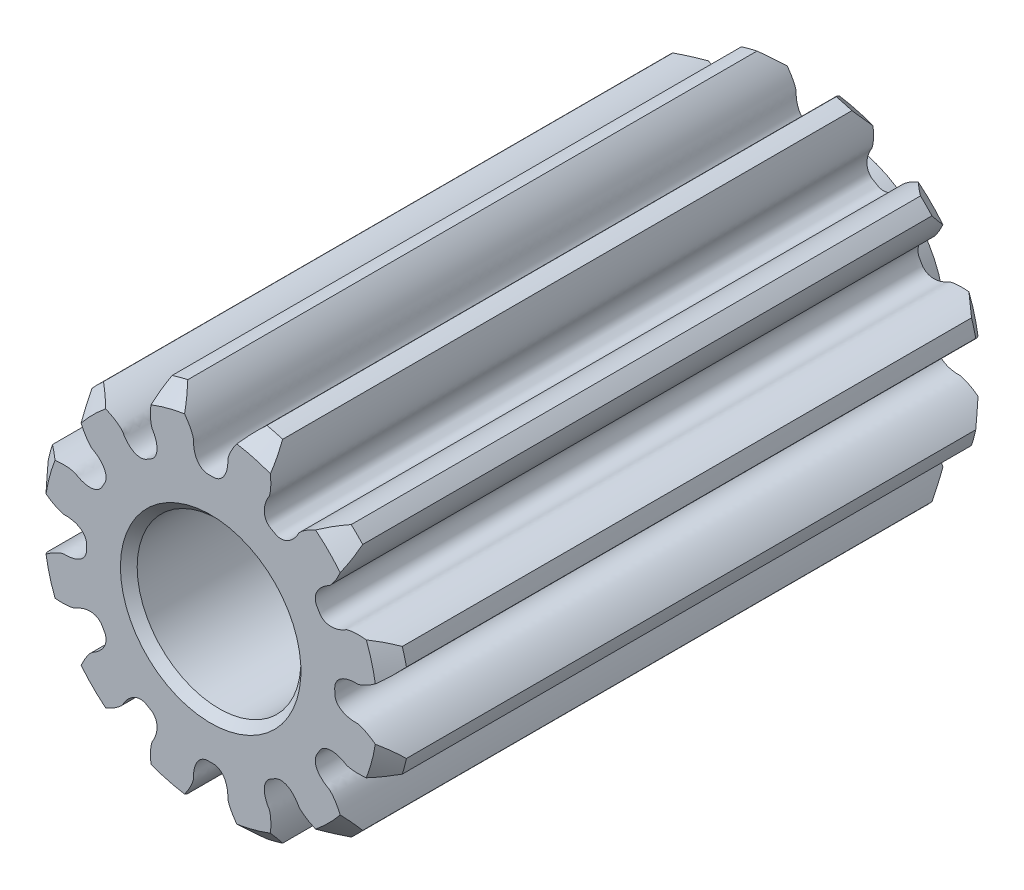
SolidWorks part; units mm, degrees
material "Plain Carbon Steel"
ref_plane "Front Plane" through (0, 0, 0) normal (0, 0, 1) x (1, 0, 0)
ref_plane "Top Plane" through (0, 0, 0) normal (0, 1, 0) x (1, 0, 0)
ref_plane "Right Plane" through (0, 0, 0) normal (1, 0, 0) x (0, 0, -1)
ref_plane "Plane1" through (0, 0, -9.1281) normal (0, 0, -1) x (-1, 0, 0)
sketch "Sketch1" plane through (0, 0, -9.1281) normal (0, 0, -1) x (-1, 0, 0)
  arc A0 (5.4254, 1.1987) -> (5.2979, 1.6746) centre (0, 0) ccw
  arc A1 (4.0992, 3.7508) -> (3.7508, 4.0992) centre (0, 0) ccw
  arc A2 (1.6746, 5.2979) -> (1.1987, 5.4254) centre (0, 0) ccw
  arc A3 (-1.1987, 5.4254) -> (-1.6746, 5.2979) centre (0, 0) ccw
  arc A4 (-3.7508, 4.0992) -> (-4.0992, 3.7508) centre (0, 0) ccw
  arc A5 (-5.2979, 1.6746) -> (-5.4254, 1.1987) centre (0, 0) ccw
  arc A6 (-5.4254, -1.1987) -> (-5.2979, -1.6746) centre (0, 0) ccw
  arc A7 (-4.0992, -3.7508) -> (-3.7508, -4.0992) centre (0, 0) ccw
  arc A8 (-1.6746, -5.2979) -> (-1.1987, -5.4254) centre (0, 0) ccw
  arc A9 (1.1987, -5.4254) -> (1.6746, -5.2979) centre (0, 0) ccw
  arc A10 (3.7508, -4.0992) -> (4.0992, -3.7508) centre (0, 0) ccw
  arc A11 (5.2979, -1.6746) -> (5.4254, -1.1987) centre (0, 0) ccw
  spline S0 degree 3 poles (5.4254, 1.1987) (5.3837, 1.151) (5.3155, 1.0775) (5.219, 0.9833) (5.1419, 0.9135) (5.067, 0.8507) (4.9949, 0.7945) (4.9257, 0.7448) (4.8601, 0.7012) (4.7982, 0.6634) (4.7404, 0.6311) (4.6871, 0.6037) (4.6385, 0.5811) (4.5949, 0.5628) (4.5566, 0.5482) (4.5124, 0.5337) (4.4425, 0.5115) (4.3737, 0.5215) (4.3208, 0.5172) (4.3005, 0.5154) (4.2805, 0.5133) (4.2608, 0.5108) (4.2414, 0.508) (4.2222, 0.5048) (4.2033, 0.5013) (4.1847, 0.4975) (4.1664, 0.4933) (4.1483, 0.4888) (4.1305, 0.4839) (4.1129, 0.4787) (4.0957, 0.4731) (4.0787, 0.4672) (4.0619, 0.4609) (4.0454, 0.4542) (4.0292, 0.4471) (4.0133, 0.4396) (3.9976, 0.4317) (3.9821, 0.4233) (3.967, 0.4145) (3.9521, 0.4052) (3.9375, 0.3954) (3.9231, 0.3851) (3.9091, 0.3742) (3.8954, 0.3627) (3.8821, 0.3507) (3.8691, 0.338) (3.8565, 0.3246) (3.8444, 0.3106) (3.8328, 0.2958) (3.8217, 0.2802) (3.8112, 0.264) (3.8014, 0.2469) (3.7925, 0.2291) (3.7843, 0.2106) (3.7771, 0.1913) (3.771, 0.1714) (3.766, 0.151) (3.7622, 0.13) (3.7597, 0.1087) (3.7586, 0.0894) (3.7583, 0.0531) (3.7599, 0) (3.7583, -0.0531) (3.7586, -0.0894) (3.7597, -0.1087) (3.7622, -0.13) (3.766, -0.151) (3.771, -0.1714) (3.7771, -0.1913) (3.7843, -0.2106) (3.7925, -0.2291) (3.8014, -0.2469) (3.8112, -0.264) (3.8217, -0.2802) (3.8328, -0.2958) (3.8444, -0.3106) (3.8565, -0.3246) (3.8691, -0.338) (3.8821, -0.3507) (3.8954, -0.3627) (3.9091, -0.3742) (3.9231, -0.3851) (3.9375, -0.3954) (3.9521, -0.4052) (3.967, -0.4145) (3.9821, -0.4233) (3.9976, -0.4317) (4.0133, -0.4396) (4.0292, -0.4471) (4.0454, -0.4542) (4.0619, -0.4609) (4.0787, -0.4672) (4.0957, -0.4731) (4.1129, -0.4787) (4.1305, -0.4839) (4.1483, -0.4888) (4.1664, -0.4933) (4.1847, -0.4975) (4.2033, -0.5013) (4.2222, -0.5048) (4.2414, -0.508) (4.2608, -0.5108) (4.2805, -0.5133) (4.3005, -0.5154) (4.3208, -0.5172) (4.3737, -0.5215) (4.4425, -0.5115) (4.5124, -0.5337) (4.5566, -0.5482) (4.5949, -0.5628) (4.6385, -0.5811) (4.6871, -0.6037) (4.7404, -0.6311) (4.7982, -0.6634) (4.8601, -0.7012) (4.9257, -0.7448) (4.9949, -0.7945) (5.067, -0.8507) (5.1419, -0.9135) (5.219, -0.9833) (5.3155, -1.0775) (5.3837, -1.151) (5.4254, -1.1987) knots 0 0 0 0 0.042267 0.066794 0.08992 0.111644 0.131967 0.150888 0.168407 0.184525 0.199242 0.212557 0.22447 0.234982 0.244092 0.251801 0.266087 0.292386 0.296963 0.301485 0.305953 0.31037 0.314735 0.319052 0.323321 0.327546 0.331727 0.335868 0.339971 0.344037 0.348071 0.352075 0.356052 0.360006 0.36394 0.367858 0.371765 0.375665 0.379562 0.383462 0.387371 0.391292 0.395233 0.399199 0.403196 0.407229 0.411306 0.415432 0.419611 0.423849 0.42815 0.432515 0.436948 0.441448 0.446012 0.450638 0.45532 0.460051 0.464821 0.469619 0.472951 0.489007 0.505064 0.508396 0.513194 0.517964 0.522694 0.527376 0.532002 0.536567 0.541066 0.545499 0.549865 0.554165 0.558403 0.562583 0.566708 0.570785 0.574819 0.578816 0.582782 0.586722 0.590644 0.594552 0.598452 0.60235 0.60625 0.610156 0.614075 0.618009 0.621963 0.62594 0.629943 0.633977 0.638044 0.642146 0.646287 0.650469 0.654693 0.658963 0.663279 0.667645 0.672061 0.676529 0.681051 0.685628 0.711928 0.726214 0.733923 0.743033 0.753545 0.765458 0.778773 0.793489 0.809607 0.827127 0.846048 0.86637 0.888095 0.91122 0.935748 0.978015 0.978015 0.978015 0.978015
  spline S1 degree 3 poles (4.0992, 3.7508) (4.0869, 3.6886) (4.0646, 3.5909) (4.0281, 3.4611) (3.9963, 3.3621) (3.9629, 3.2702) (3.9284, 3.1855) (3.8934, 3.1079) (3.8583, 3.0373) (3.8236, 2.9736) (3.7898, 2.9167) (3.7573, 2.8664) (3.7265, 2.8225) (3.698, 2.7848) (3.6721, 2.753) (3.641, 2.7184) (3.5916, 2.6642) (3.5269, 2.6385) (3.4833, 2.6083) (3.4666, 2.5966) (3.4504, 2.5848) (3.4346, 2.5728) (3.4191, 2.5606) (3.4041, 2.5483) (3.3895, 2.5358) (3.3753, 2.5232) (3.3615, 2.5104) (3.3481, 2.4975) (3.3351, 2.4843) (3.3225, 2.4711) (3.3104, 2.4576) (3.2986, 2.4439) (3.2873, 2.4301) (3.2764, 2.416) (3.2659, 2.4018) (3.2558, 2.3873) (3.2462, 2.3726) (3.237, 2.3576) (3.2283, 2.3424) (3.22, 2.3269) (3.2122, 2.3111) (3.205, 2.295) (3.1983, 2.2786) (3.1922, 2.2619) (3.1866, 2.2447) (3.1817, 2.2272) (3.1775, 2.2094) (3.1741, 2.1911) (3.1714, 2.1725) (3.1695, 2.1535) (3.1686, 2.1342) (3.1687, 2.1146) (3.1698, 2.0946) (3.172, 2.0745) (3.1754, 2.0543) (3.1801, 2.034) (3.186, 2.0137) (3.1931, 1.9937) (3.2016, 1.974) (3.2104, 1.9567) (3.2282, 1.9252) (3.2562, 1.88) (3.2814, 1.8331) (3.2998, 1.8019) (3.3103, 1.7857) (3.3232, 1.7685) (3.3369, 1.7522) (3.3515, 1.737) (3.3668, 1.7229) (3.3826, 1.7098) (3.3989, 1.6978) (3.4156, 1.6869) (3.4326, 1.677) (3.4498, 1.6681) (3.4671, 1.6602) (3.4846, 1.6532) (3.5022, 1.6471) (3.5197, 1.6418) (3.5373, 1.6373) (3.5549, 1.6336) (3.5725, 1.6305) (3.5901, 1.6281) (3.6076, 1.6263) (3.6252, 1.6251) (3.6427, 1.6245) (3.6603, 1.6245) (3.6778, 1.625) (3.6954, 1.6259) (3.7129, 1.6274) (3.7305, 1.6294) (3.7482, 1.6318) (3.7658, 1.6347) (3.7835, 1.6381) (3.8013, 1.6419) (3.8191, 1.6461) (3.8369, 1.6508) (3.8548, 1.6559) (3.8728, 1.6615) (3.8908, 1.6675) (3.909, 1.6739) (3.9271, 1.6808) (3.9454, 1.688) (3.9637, 1.6957) (3.9821, 1.7039) (4.0005, 1.7125) (4.0485, 1.7352) (4.1031, 1.7783) (4.1747, 1.794) (4.2202, 1.8036) (4.2607, 1.8101) (4.3076, 1.816) (4.361, 1.8207) (4.4209, 1.8237) (4.4871, 1.8245) (4.5596, 1.8227) (4.6382, 1.8178) (4.7229, 1.8093) (4.8135, 1.7968) (4.9098, 1.7798) (5.0115, 1.7579) (5.1422, 1.7246) (5.2379, 1.695) (5.2979, 1.6746) knots 0 0 0 0 0.042267 0.066794 0.08992 0.111644 0.131967 0.150888 0.168407 0.184525 0.199242 0.212557 0.22447 0.234982 0.244092 0.251801 0.266087 0.292386 0.296963 0.301485 0.305953 0.31037 0.314735 0.319052 0.323321 0.327546 0.331727 0.335868 0.339971 0.344037 0.348071 0.352075 0.356052 0.360006 0.36394 0.367858 0.371765 0.375665 0.379562 0.383462 0.387371 0.391292 0.395233 0.399199 0.403196 0.407229 0.411306 0.415432 0.419611 0.423849 0.42815 0.432515 0.436948 0.441448 0.446012 0.450638 0.45532 0.460051 0.464821 0.469619 0.472951 0.489007 0.505064 0.508396 0.513194 0.517964 0.522694 0.527376 0.532002 0.536567 0.541066 0.545499 0.549865 0.554165 0.558403 0.562583 0.566708 0.570785 0.574819 0.578816 0.582782 0.586722 0.590644 0.594552 0.598452 0.60235 0.60625 0.610156 0.614075 0.618009 0.621963 0.62594 0.629943 0.633977 0.638044 0.642146 0.646287 0.650469 0.654693 0.658963 0.663279 0.667645 0.672061 0.676529 0.681051 0.685628 0.711928 0.726214 0.733923 0.743033 0.753545 0.765458 0.778773 0.793489 0.809607 0.827127 0.846048 0.86637 0.888095 0.91122 0.935748 0.978015 0.978015 0.978015 0.978015
  spline S2 degree 3 poles (1.6746, 5.2979) (1.695, 5.2379) (1.7246, 5.1422) (1.7579, 5.0115) (1.7798, 4.9098) (1.7968, 4.8135) (1.8093, 4.7229) (1.8178, 4.6382) (1.8227, 4.5596) (1.8245, 4.4871) (1.8237, 4.4209) (1.8207, 4.361) (1.816, 4.3076) (1.8101, 4.2607) (1.8036, 4.2202) (1.794, 4.1747) (1.7783, 4.1031) (1.7352, 4.0485) (1.7125, 4.0005) (1.7039, 3.9821) (1.6957, 3.9637) (1.688, 3.9454) (1.6808, 3.9271) (1.6739, 3.909) (1.6675, 3.8908) (1.6615, 3.8728) (1.6559, 3.8548) (1.6508, 3.8369) (1.6461, 3.8191) (1.6419, 3.8013) (1.6381, 3.7835) (1.6347, 3.7658) (1.6318, 3.7482) (1.6294, 3.7305) (1.6274, 3.7129) (1.6259, 3.6954) (1.625, 3.6778) (1.6245, 3.6603) (1.6245, 3.6427) (1.6251, 3.6252) (1.6263, 3.6076) (1.6281, 3.5901) (1.6305, 3.5725) (1.6336, 3.5549) (1.6373, 3.5373) (1.6418, 3.5197) (1.6471, 3.5022) (1.6532, 3.4846) (1.6602, 3.4671) (1.6681, 3.4498) (1.677, 3.4326) (1.6869, 3.4156) (1.6978, 3.3989) (1.7098, 3.3826) (1.7229, 3.3668) (1.737, 3.3515) (1.7522, 3.3369) (1.7685, 3.3232) (1.7857, 3.3103) (1.8019, 3.2998) (1.8331, 3.2814) (1.88, 3.2562) (1.9252, 3.2282) (1.9567, 3.2104) (1.974, 3.2016) (1.9937, 3.1931) (2.0137, 3.186) (2.034, 3.1801) (2.0543, 3.1754) (2.0745, 3.172) (2.0946, 3.1698) (2.1146, 3.1687) (2.1342, 3.1686) (2.1535, 3.1695) (2.1725, 3.1714) (2.1911, 3.1741) (2.2094, 3.1775) (2.2272, 3.1817) (2.2447, 3.1866) (2.2619, 3.1922) (2.2786, 3.1983) (2.295, 3.205) (2.3111, 3.2122) (2.3269, 3.22) (2.3424, 3.2283) (2.3576, 3.237) (2.3726, 3.2462) (2.3873, 3.2558) (2.4018, 3.2659) (2.416, 3.2764) (2.4301, 3.2873) (2.4439, 3.2986) (2.4576, 3.3104) (2.4711, 3.3225) (2.4843, 3.3351) (2.4975, 3.3481) (2.5104, 3.3615) (2.5232, 3.3753) (2.5358, 3.3895) (2.5483, 3.4041) (2.5606, 3.4191) (2.5728, 3.4346) (2.5848, 3.4504) (2.5966, 3.4666) (2.6083, 3.4833) (2.6385, 3.5269) (2.6642, 3.5916) (2.7184, 3.641) (2.753, 3.6721) (2.7848, 3.698) (2.8225, 3.7265) (2.8664, 3.7573) (2.9167, 3.7898) (2.9736, 3.8236) (3.0373, 3.8583) (3.1079, 3.8934) (3.1855, 3.9284) (3.2702, 3.9629) (3.3621, 3.9963) (3.4611, 4.0281) (3.5909, 4.0646) (3.6886, 4.0869) (3.7508, 4.0992) knots 0 0 0 0 0.042267 0.066794 0.08992 0.111644 0.131967 0.150888 0.168407 0.184525 0.199242 0.212557 0.22447 0.234982 0.244092 0.251801 0.266087 0.292386 0.296963 0.301485 0.305953 0.31037 0.314735 0.319052 0.323321 0.327546 0.331727 0.335868 0.339971 0.344037 0.348071 0.352075 0.356052 0.360006 0.36394 0.367858 0.371765 0.375665 0.379562 0.383462 0.387371 0.391292 0.395233 0.399199 0.403196 0.407229 0.411306 0.415432 0.419611 0.423849 0.42815 0.432515 0.436948 0.441448 0.446012 0.450638 0.45532 0.460051 0.464821 0.469619 0.472951 0.489007 0.505064 0.508396 0.513194 0.517964 0.522694 0.527376 0.532002 0.536567 0.541066 0.545499 0.549865 0.554165 0.558403 0.562583 0.566708 0.570785 0.574819 0.578816 0.582782 0.586722 0.590644 0.594552 0.598452 0.60235 0.60625 0.610156 0.614075 0.618009 0.621963 0.62594 0.629943 0.633977 0.638044 0.642146 0.646287 0.650469 0.654693 0.658963 0.663279 0.667645 0.672061 0.676529 0.681051 0.685628 0.711928 0.726214 0.733923 0.743033 0.753545 0.765458 0.778773 0.793489 0.809607 0.827127 0.846048 0.86637 0.888095 0.91122 0.935748 0.978015 0.978015 0.978015 0.978015
  spline S3 degree 3 poles (-1.1987, 5.4254) (-1.151, 5.3837) (-1.0775, 5.3155) (-0.9833, 5.219) (-0.9135, 5.1419) (-0.8507, 5.067) (-0.7945, 4.9949) (-0.7448, 4.9257) (-0.7012, 4.8601) (-0.6634, 4.7982) (-0.6311, 4.7404) (-0.6037, 4.6871) (-0.5811, 4.6385) (-0.5628, 4.5949) (-0.5482, 4.5566) (-0.5337, 4.5124) (-0.5115, 4.4425) (-0.5215, 4.3737) (-0.5172, 4.3208) (-0.5154, 4.3005) (-0.5133, 4.2805) (-0.5108, 4.2608) (-0.508, 4.2414) (-0.5048, 4.2222) (-0.5013, 4.2033) (-0.4975, 4.1847) (-0.4933, 4.1664) (-0.4888, 4.1483) (-0.4839, 4.1305) (-0.4787, 4.1129) (-0.4731, 4.0957) (-0.4672, 4.0787) (-0.4609, 4.0619) (-0.4542, 4.0454) (-0.4471, 4.0292) (-0.4396, 4.0133) (-0.4317, 3.9976) (-0.4233, 3.9821) (-0.4145, 3.967) (-0.4052, 3.9521) (-0.3954, 3.9375) (-0.3851, 3.9231) (-0.3742, 3.9091) (-0.3627, 3.8954) (-0.3507, 3.8821) (-0.338, 3.8691) (-0.3246, 3.8565) (-0.3106, 3.8444) (-0.2958, 3.8328) (-0.2802, 3.8217) (-0.264, 3.8112) (-0.2469, 3.8014) (-0.2291, 3.7925) (-0.2106, 3.7843) (-0.1913, 3.7771) (-0.1714, 3.771) (-0.151, 3.766) (-0.13, 3.7622) (-0.1087, 3.7597) (-0.0894, 3.7586) (-0.0531, 3.7583) (0, 3.7599) (0.0531, 3.7583) (0.0894, 3.7586) (0.1087, 3.7597) (0.13, 3.7622) (0.151, 3.766) (0.1714, 3.771) (0.1913, 3.7771) (0.2106, 3.7843) (0.2291, 3.7925) (0.2469, 3.8014) (0.264, 3.8112) (0.2802, 3.8217) (0.2958, 3.8328) (0.3106, 3.8444) (0.3246, 3.8565) (0.338, 3.8691) (0.3507, 3.8821) (0.3627, 3.8954) (0.3742, 3.9091) (0.3851, 3.9231) (0.3954, 3.9375) (0.4052, 3.9521) (0.4145, 3.967) (0.4233, 3.9821) (0.4317, 3.9976) (0.4396, 4.0133) (0.4471, 4.0292) (0.4542, 4.0454) (0.4609, 4.0619) (0.4672, 4.0787) (0.4731, 4.0957) (0.4787, 4.1129) (0.4839, 4.1305) (0.4888, 4.1483) (0.4933, 4.1664) (0.4975, 4.1847) (0.5013, 4.2033) (0.5048, 4.2222) (0.508, 4.2414) (0.5108, 4.2608) (0.5133, 4.2805) (0.5154, 4.3005) (0.5172, 4.3208) (0.5215, 4.3737) (0.5115, 4.4425) (0.5337, 4.5124) (0.5482, 4.5566) (0.5628, 4.5949) (0.5811, 4.6385) (0.6037, 4.6871) (0.6311, 4.7404) (0.6634, 4.7982) (0.7012, 4.8601) (0.7448, 4.9257) (0.7945, 4.9949) (0.8507, 5.067) (0.9135, 5.1419) (0.9833, 5.219) (1.0775, 5.3155) (1.151, 5.3837) (1.1987, 5.4254) knots 0 0 0 0 0.042267 0.066794 0.08992 0.111644 0.131967 0.150888 0.168407 0.184525 0.199242 0.212557 0.22447 0.234982 0.244092 0.251801 0.266087 0.292386 0.296963 0.301485 0.305953 0.31037 0.314735 0.319052 0.323321 0.327546 0.331727 0.335868 0.339971 0.344037 0.348071 0.352075 0.356052 0.360006 0.36394 0.367858 0.371765 0.375665 0.379562 0.383462 0.387371 0.391292 0.395233 0.399199 0.403196 0.407229 0.411306 0.415432 0.419611 0.423849 0.42815 0.432515 0.436948 0.441448 0.446012 0.450638 0.45532 0.460051 0.464821 0.469619 0.472951 0.489007 0.505064 0.508396 0.513194 0.517964 0.522694 0.527376 0.532002 0.536567 0.541066 0.545499 0.549865 0.554165 0.558403 0.562583 0.566708 0.570785 0.574819 0.578816 0.582782 0.586722 0.590644 0.594552 0.598452 0.60235 0.60625 0.610156 0.614075 0.618009 0.621963 0.62594 0.629943 0.633977 0.638044 0.642146 0.646287 0.650469 0.654693 0.658963 0.663279 0.667645 0.672061 0.676529 0.681051 0.685628 0.711928 0.726214 0.733923 0.743033 0.753545 0.765458 0.778773 0.793489 0.809607 0.827127 0.846048 0.86637 0.888095 0.91122 0.935748 0.978015 0.978015 0.978015 0.978015
  spline S4 degree 3 poles (-3.7508, 4.0992) (-3.6886, 4.0869) (-3.5909, 4.0646) (-3.4611, 4.0281) (-3.3621, 3.9963) (-3.2702, 3.9629) (-3.1855, 3.9284) (-3.1079, 3.8934) (-3.0373, 3.8583) (-2.9736, 3.8236) (-2.9167, 3.7898) (-2.8664, 3.7573) (-2.8225, 3.7265) (-2.7848, 3.698) (-2.753, 3.6721) (-2.7184, 3.641) (-2.6642, 3.5916) (-2.6385, 3.5269) (-2.6083, 3.4833) (-2.5966, 3.4666) (-2.5848, 3.4504) (-2.5728, 3.4346) (-2.5606, 3.4191) (-2.5483, 3.4041) (-2.5358, 3.3895) (-2.5232, 3.3753) (-2.5104, 3.3615) (-2.4975, 3.3481) (-2.4843, 3.3351) (-2.4711, 3.3225) (-2.4576, 3.3104) (-2.4439, 3.2986) (-2.4301, 3.2873) (-2.416, 3.2764) (-2.4018, 3.2659) (-2.3873, 3.2558) (-2.3726, 3.2462) (-2.3576, 3.237) (-2.3424, 3.2283) (-2.3269, 3.22) (-2.3111, 3.2122) (-2.295, 3.205) (-2.2786, 3.1983) (-2.2619, 3.1922) (-2.2447, 3.1866) (-2.2272, 3.1817) (-2.2094, 3.1775) (-2.1911, 3.1741) (-2.1725, 3.1714) (-2.1535, 3.1695) (-2.1342, 3.1686) (-2.1146, 3.1687) (-2.0946, 3.1698) (-2.0745, 3.172) (-2.0543, 3.1754) (-2.034, 3.1801) (-2.0137, 3.186) (-1.9937, 3.1931) (-1.974, 3.2016) (-1.9567, 3.2104) (-1.9252, 3.2282) (-1.88, 3.2562) (-1.8331, 3.2814) (-1.8019, 3.2998) (-1.7857, 3.3103) (-1.7685, 3.3232) (-1.7522, 3.3369) (-1.737, 3.3515) (-1.7229, 3.3668) (-1.7098, 3.3826) (-1.6978, 3.3989) (-1.6869, 3.4156) (-1.677, 3.4326) (-1.6681, 3.4498) (-1.6602, 3.4671) (-1.6532, 3.4846) (-1.6471, 3.5022) (-1.6418, 3.5197) (-1.6373, 3.5373) (-1.6336, 3.5549) (-1.6305, 3.5725) (-1.6281, 3.5901) (-1.6263, 3.6076) (-1.6251, 3.6252) (-1.6245, 3.6427) (-1.6245, 3.6603) (-1.625, 3.6778) (-1.6259, 3.6954) (-1.6274, 3.7129) (-1.6294, 3.7305) (-1.6318, 3.7482) (-1.6347, 3.7658) (-1.6381, 3.7835) (-1.6419, 3.8013) (-1.6461, 3.8191) (-1.6508, 3.8369) (-1.6559, 3.8548) (-1.6615, 3.8728) (-1.6675, 3.8908) (-1.6739, 3.909) (-1.6808, 3.9271) (-1.688, 3.9454) (-1.6957, 3.9637) (-1.7039, 3.9821) (-1.7125, 4.0005) (-1.7352, 4.0485) (-1.7783, 4.1031) (-1.794, 4.1747) (-1.8036, 4.2202) (-1.8101, 4.2607) (-1.816, 4.3076) (-1.8207, 4.361) (-1.8237, 4.4209) (-1.8245, 4.4871) (-1.8227, 4.5596) (-1.8178, 4.6382) (-1.8093, 4.7229) (-1.7968, 4.8135) (-1.7798, 4.9098) (-1.7579, 5.0115) (-1.7246, 5.1422) (-1.695, 5.2379) (-1.6746, 5.2979) knots 0 0 0 0 0.042267 0.066794 0.08992 0.111644 0.131967 0.150888 0.168407 0.184525 0.199242 0.212557 0.22447 0.234982 0.244092 0.251801 0.266087 0.292386 0.296963 0.301485 0.305953 0.31037 0.314735 0.319052 0.323321 0.327546 0.331727 0.335868 0.339971 0.344037 0.348071 0.352075 0.356052 0.360006 0.36394 0.367858 0.371765 0.375665 0.379562 0.383462 0.387371 0.391292 0.395233 0.399199 0.403196 0.407229 0.411306 0.415432 0.419611 0.423849 0.42815 0.432515 0.436948 0.441448 0.446012 0.450638 0.45532 0.460051 0.464821 0.469619 0.472951 0.489007 0.505064 0.508396 0.513194 0.517964 0.522694 0.527376 0.532002 0.536567 0.541066 0.545499 0.549865 0.554165 0.558403 0.562583 0.566708 0.570785 0.574819 0.578816 0.582782 0.586722 0.590644 0.594552 0.598452 0.60235 0.60625 0.610156 0.614075 0.618009 0.621963 0.62594 0.629943 0.633977 0.638044 0.642146 0.646287 0.650469 0.654693 0.658963 0.663279 0.667645 0.672061 0.676529 0.681051 0.685628 0.711928 0.726214 0.733923 0.743033 0.753545 0.765458 0.778773 0.793489 0.809607 0.827127 0.846048 0.86637 0.888095 0.91122 0.935748 0.978015 0.978015 0.978015 0.978015
  spline S5 degree 3 poles (-5.2979, 1.6746) (-5.2379, 1.695) (-5.1422, 1.7246) (-5.0115, 1.7579) (-4.9098, 1.7798) (-4.8135, 1.7968) (-4.7229, 1.8093) (-4.6382, 1.8178) (-4.5596, 1.8227) (-4.4871, 1.8245) (-4.4209, 1.8237) (-4.361, 1.8207) (-4.3076, 1.816) (-4.2607, 1.8101) (-4.2202, 1.8036) (-4.1747, 1.794) (-4.1031, 1.7783) (-4.0485, 1.7352) (-4.0005, 1.7125) (-3.9821, 1.7039) (-3.9637, 1.6957) (-3.9454, 1.688) (-3.9271, 1.6808) (-3.909, 1.6739) (-3.8908, 1.6675) (-3.8728, 1.6615) (-3.8548, 1.6559) (-3.8369, 1.6508) (-3.8191, 1.6461) (-3.8013, 1.6419) (-3.7835, 1.6381) (-3.7658, 1.6347) (-3.7482, 1.6318) (-3.7305, 1.6294) (-3.7129, 1.6274) (-3.6954, 1.6259) (-3.6778, 1.625) (-3.6603, 1.6245) (-3.6427, 1.6245) (-3.6252, 1.6251) (-3.6076, 1.6263) (-3.5901, 1.6281) (-3.5725, 1.6305) (-3.5549, 1.6336) (-3.5373, 1.6373) (-3.5197, 1.6418) (-3.5022, 1.6471) (-3.4846, 1.6532) (-3.4671, 1.6602) (-3.4498, 1.6681) (-3.4326, 1.677) (-3.4156, 1.6869) (-3.3989, 1.6978) (-3.3826, 1.7098) (-3.3668, 1.7229) (-3.3515, 1.737) (-3.3369, 1.7522) (-3.3232, 1.7685) (-3.3103, 1.7857) (-3.2998, 1.8019) (-3.2814, 1.8331) (-3.2562, 1.88) (-3.2282, 1.9252) (-3.2104, 1.9567) (-3.2016, 1.974) (-3.1931, 1.9937) (-3.186, 2.0137) (-3.1801, 2.034) (-3.1754, 2.0543) (-3.172, 2.0745) (-3.1698, 2.0946) (-3.1687, 2.1146) (-3.1686, 2.1342) (-3.1695, 2.1535) (-3.1714, 2.1725) (-3.1741, 2.1911) (-3.1775, 2.2094) (-3.1817, 2.2272) (-3.1866, 2.2447) (-3.1922, 2.2619) (-3.1983, 2.2786) (-3.205, 2.295) (-3.2122, 2.3111) (-3.22, 2.3269) (-3.2283, 2.3424) (-3.237, 2.3576) (-3.2462, 2.3726) (-3.2558, 2.3873) (-3.2659, 2.4018) (-3.2764, 2.416) (-3.2873, 2.4301) (-3.2986, 2.4439) (-3.3104, 2.4576) (-3.3225, 2.4711) (-3.3351, 2.4843) (-3.3481, 2.4975) (-3.3615, 2.5104) (-3.3753, 2.5232) (-3.3895, 2.5358) (-3.4041, 2.5483) (-3.4191, 2.5606) (-3.4346, 2.5728) (-3.4504, 2.5848) (-3.4666, 2.5966) (-3.4833, 2.6083) (-3.5269, 2.6385) (-3.5916, 2.6642) (-3.641, 2.7184) (-3.6721, 2.753) (-3.698, 2.7848) (-3.7265, 2.8225) (-3.7573, 2.8664) (-3.7898, 2.9167) (-3.8236, 2.9736) (-3.8583, 3.0373) (-3.8934, 3.1079) (-3.9284, 3.1855) (-3.9629, 3.2702) (-3.9963, 3.3621) (-4.0281, 3.4611) (-4.0646, 3.5909) (-4.0869, 3.6886) (-4.0992, 3.7508) knots 0 0 0 0 0.042267 0.066794 0.08992 0.111644 0.131967 0.150888 0.168407 0.184525 0.199242 0.212557 0.22447 0.234982 0.244092 0.251801 0.266087 0.292386 0.296963 0.301485 0.305953 0.31037 0.314735 0.319052 0.323321 0.327546 0.331727 0.335868 0.339971 0.344037 0.348071 0.352075 0.356052 0.360006 0.36394 0.367858 0.371765 0.375665 0.379562 0.383462 0.387371 0.391292 0.395233 0.399199 0.403196 0.407229 0.411306 0.415432 0.419611 0.423849 0.42815 0.432515 0.436948 0.441448 0.446012 0.450638 0.45532 0.460051 0.464821 0.469619 0.472951 0.489007 0.505064 0.508396 0.513194 0.517964 0.522694 0.527376 0.532002 0.536567 0.541066 0.545499 0.549865 0.554165 0.558403 0.562583 0.566708 0.570785 0.574819 0.578816 0.582782 0.586722 0.590644 0.594552 0.598452 0.60235 0.60625 0.610156 0.614075 0.618009 0.621963 0.62594 0.629943 0.633977 0.638044 0.642146 0.646287 0.650469 0.654693 0.658963 0.663279 0.667645 0.672061 0.676529 0.681051 0.685628 0.711928 0.726214 0.733923 0.743033 0.753545 0.765458 0.778773 0.793489 0.809607 0.827127 0.846048 0.86637 0.888095 0.91122 0.935748 0.978015 0.978015 0.978015 0.978015
  spline S6 degree 3 poles (-5.4254, -1.1987) (-5.3837, -1.151) (-5.3155, -1.0775) (-5.219, -0.9833) (-5.1419, -0.9135) (-5.067, -0.8507) (-4.9949, -0.7945) (-4.9257, -0.7448) (-4.8601, -0.7012) (-4.7982, -0.6634) (-4.7404, -0.6311) (-4.6871, -0.6037) (-4.6385, -0.5811) (-4.5949, -0.5628) (-4.5566, -0.5482) (-4.5124, -0.5337) (-4.4425, -0.5115) (-4.3737, -0.5215) (-4.3208, -0.5172) (-4.3005, -0.5154) (-4.2805, -0.5133) (-4.2608, -0.5108) (-4.2414, -0.508) (-4.2222, -0.5048) (-4.2033, -0.5013) (-4.1847, -0.4975) (-4.1664, -0.4933) (-4.1483, -0.4888) (-4.1305, -0.4839) (-4.1129, -0.4787) (-4.0957, -0.4731) (-4.0787, -0.4672) (-4.0619, -0.4609) (-4.0454, -0.4542) (-4.0292, -0.4471) (-4.0133, -0.4396) (-3.9976, -0.4317) (-3.9821, -0.4233) (-3.967, -0.4145) (-3.9521, -0.4052) (-3.9375, -0.3954) (-3.9231, -0.3851) (-3.9091, -0.3742) (-3.8954, -0.3627) (-3.8821, -0.3507) (-3.8691, -0.338) (-3.8565, -0.3246) (-3.8444, -0.3106) (-3.8328, -0.2958) (-3.8217, -0.2802) (-3.8112, -0.264) (-3.8014, -0.2469) (-3.7925, -0.2291) (-3.7843, -0.2106) (-3.7771, -0.1913) (-3.771, -0.1714) (-3.766, -0.151) (-3.7622, -0.13) (-3.7597, -0.1087) (-3.7586, -0.0894) (-3.7583, -0.0531) (-3.7599, 0) (-3.7583, 0.0531) (-3.7586, 0.0894) (-3.7597, 0.1087) (-3.7622, 0.13) (-3.766, 0.151) (-3.771, 0.1714) (-3.7771, 0.1913) (-3.7843, 0.2106) (-3.7925, 0.2291) (-3.8014, 0.2469) (-3.8112, 0.264) (-3.8217, 0.2802) (-3.8328, 0.2958) (-3.8444, 0.3106) (-3.8565, 0.3246) (-3.8691, 0.338) (-3.8821, 0.3507) (-3.8954, 0.3627) (-3.9091, 0.3742) (-3.9231, 0.3851) (-3.9375, 0.3954) (-3.9521, 0.4052) (-3.967, 0.4145) (-3.9821, 0.4233) (-3.9976, 0.4317) (-4.0133, 0.4396) (-4.0292, 0.4471) (-4.0454, 0.4542) (-4.0619, 0.4609) (-4.0787, 0.4672) (-4.0957, 0.4731) (-4.1129, 0.4787) (-4.1305, 0.4839) (-4.1483, 0.4888) (-4.1664, 0.4933) (-4.1847, 0.4975) (-4.2033, 0.5013) (-4.2222, 0.5048) (-4.2414, 0.508) (-4.2608, 0.5108) (-4.2805, 0.5133) (-4.3005, 0.5154) (-4.3208, 0.5172) (-4.3737, 0.5215) (-4.4425, 0.5115) (-4.5124, 0.5337) (-4.5566, 0.5482) (-4.5949, 0.5628) (-4.6385, 0.5811) (-4.6871, 0.6037) (-4.7404, 0.6311) (-4.7982, 0.6634) (-4.8601, 0.7012) (-4.9257, 0.7448) (-4.9949, 0.7945) (-5.067, 0.8507) (-5.1419, 0.9135) (-5.219, 0.9833) (-5.3155, 1.0775) (-5.3837, 1.151) (-5.4254, 1.1987) knots 0 0 0 0 0.042267 0.066794 0.08992 0.111644 0.131967 0.150888 0.168407 0.184525 0.199242 0.212557 0.22447 0.234982 0.244092 0.251801 0.266087 0.292386 0.296963 0.301485 0.305953 0.31037 0.314735 0.319052 0.323321 0.327546 0.331727 0.335868 0.339971 0.344037 0.348071 0.352075 0.356052 0.360006 0.36394 0.367858 0.371765 0.375665 0.379562 0.383462 0.387371 0.391292 0.395233 0.399199 0.403196 0.407229 0.411306 0.415432 0.419611 0.423849 0.42815 0.432515 0.436948 0.441448 0.446012 0.450638 0.45532 0.460051 0.464821 0.469619 0.472951 0.489007 0.505064 0.508396 0.513194 0.517964 0.522694 0.527376 0.532002 0.536567 0.541066 0.545499 0.549865 0.554165 0.558403 0.562583 0.566708 0.570785 0.574819 0.578816 0.582782 0.586722 0.590644 0.594552 0.598452 0.60235 0.60625 0.610156 0.614075 0.618009 0.621963 0.62594 0.629943 0.633977 0.638044 0.642146 0.646287 0.650469 0.654693 0.658963 0.663279 0.667645 0.672061 0.676529 0.681051 0.685628 0.711928 0.726214 0.733923 0.743033 0.753545 0.765458 0.778773 0.793489 0.809607 0.827127 0.846048 0.86637 0.888095 0.91122 0.935748 0.978015 0.978015 0.978015 0.978015
  spline S7 degree 3 poles (-4.0992, -3.7508) (-4.0869, -3.6886) (-4.0646, -3.5909) (-4.0281, -3.4611) (-3.9963, -3.3621) (-3.9629, -3.2702) (-3.9284, -3.1855) (-3.8934, -3.1079) (-3.8583, -3.0373) (-3.8236, -2.9736) (-3.7898, -2.9167) (-3.7573, -2.8664) (-3.7265, -2.8225) (-3.698, -2.7848) (-3.6721, -2.753) (-3.641, -2.7184) (-3.5916, -2.6642) (-3.5269, -2.6385) (-3.4833, -2.6083) (-3.4666, -2.5966) (-3.4504, -2.5848) (-3.4346, -2.5728) (-3.4191, -2.5606) (-3.4041, -2.5483) (-3.3895, -2.5358) (-3.3753, -2.5232) (-3.3615, -2.5104) (-3.3481, -2.4975) (-3.3351, -2.4843) (-3.3225, -2.4711) (-3.3104, -2.4576) (-3.2986, -2.4439) (-3.2873, -2.4301) (-3.2764, -2.416) (-3.2659, -2.4018) (-3.2558, -2.3873) (-3.2462, -2.3726) (-3.237, -2.3576) (-3.2283, -2.3424) (-3.22, -2.3269) (-3.2122, -2.3111) (-3.205, -2.295) (-3.1983, -2.2786) (-3.1922, -2.2619) (-3.1866, -2.2447) (-3.1817, -2.2272) (-3.1775, -2.2094) (-3.1741, -2.1911) (-3.1714, -2.1725) (-3.1695, -2.1535) (-3.1686, -2.1342) (-3.1687, -2.1146) (-3.1698, -2.0946) (-3.172, -2.0745) (-3.1754, -2.0543) (-3.1801, -2.034) (-3.186, -2.0137) (-3.1931, -1.9937) (-3.2016, -1.974) (-3.2104, -1.9567) (-3.2282, -1.9252) (-3.2562, -1.88) (-3.2814, -1.8331) (-3.2998, -1.8019) (-3.3103, -1.7857) (-3.3232, -1.7685) (-3.3369, -1.7522) (-3.3515, -1.737) (-3.3668, -1.7229) (-3.3826, -1.7098) (-3.3989, -1.6978) (-3.4156, -1.6869) (-3.4326, -1.677) (-3.4498, -1.6681) (-3.4671, -1.6602) (-3.4846, -1.6532) (-3.5022, -1.6471) (-3.5197, -1.6418) (-3.5373, -1.6373) (-3.5549, -1.6336) (-3.5725, -1.6305) (-3.5901, -1.6281) (-3.6076, -1.6263) (-3.6252, -1.6251) (-3.6427, -1.6245) (-3.6603, -1.6245) (-3.6778, -1.625) (-3.6954, -1.6259) (-3.7129, -1.6274) (-3.7305, -1.6294) (-3.7482, -1.6318) (-3.7658, -1.6347) (-3.7835, -1.6381) (-3.8013, -1.6419) (-3.8191, -1.6461) (-3.8369, -1.6508) (-3.8548, -1.6559) (-3.8728, -1.6615) (-3.8908, -1.6675) (-3.909, -1.6739) (-3.9271, -1.6808) (-3.9454, -1.688) (-3.9637, -1.6957) (-3.9821, -1.7039) (-4.0005, -1.7125) (-4.0485, -1.7352) (-4.1031, -1.7783) (-4.1747, -1.794) (-4.2202, -1.8036) (-4.2607, -1.8101) (-4.3076, -1.816) (-4.361, -1.8207) (-4.4209, -1.8237) (-4.4871, -1.8245) (-4.5596, -1.8227) (-4.6382, -1.8178) (-4.7229, -1.8093) (-4.8135, -1.7968) (-4.9098, -1.7798) (-5.0115, -1.7579) (-5.1422, -1.7246) (-5.2379, -1.695) (-5.2979, -1.6746) knots 0 0 0 0 0.042267 0.066794 0.08992 0.111644 0.131967 0.150888 0.168407 0.184525 0.199242 0.212557 0.22447 0.234982 0.244092 0.251801 0.266087 0.292386 0.296963 0.301485 0.305953 0.31037 0.314735 0.319052 0.323321 0.327546 0.331727 0.335868 0.339971 0.344037 0.348071 0.352075 0.356052 0.360006 0.36394 0.367858 0.371765 0.375665 0.379562 0.383462 0.387371 0.391292 0.395233 0.399199 0.403196 0.407229 0.411306 0.415432 0.419611 0.423849 0.42815 0.432515 0.436948 0.441448 0.446012 0.450638 0.45532 0.460051 0.464821 0.469619 0.472951 0.489007 0.505064 0.508396 0.513194 0.517964 0.522694 0.527376 0.532002 0.536567 0.541066 0.545499 0.549865 0.554165 0.558403 0.562583 0.566708 0.570785 0.574819 0.578816 0.582782 0.586722 0.590644 0.594552 0.598452 0.60235 0.60625 0.610156 0.614075 0.618009 0.621963 0.62594 0.629943 0.633977 0.638044 0.642146 0.646287 0.650469 0.654693 0.658963 0.663279 0.667645 0.672061 0.676529 0.681051 0.685628 0.711928 0.726214 0.733923 0.743033 0.753545 0.765458 0.778773 0.793489 0.809607 0.827127 0.846048 0.86637 0.888095 0.91122 0.935748 0.978015 0.978015 0.978015 0.978015
  spline S8 degree 3 poles (-1.6746, -5.2979) (-1.695, -5.2379) (-1.7246, -5.1422) (-1.7579, -5.0115) (-1.7798, -4.9098) (-1.7968, -4.8135) (-1.8093, -4.7229) (-1.8178, -4.6382) (-1.8227, -4.5596) (-1.8245, -4.4871) (-1.8237, -4.4209) (-1.8207, -4.361) (-1.816, -4.3076) (-1.8101, -4.2607) (-1.8036, -4.2202) (-1.794, -4.1747) (-1.7783, -4.1031) (-1.7352, -4.0485) (-1.7125, -4.0005) (-1.7039, -3.9821) (-1.6957, -3.9637) (-1.688, -3.9454) (-1.6808, -3.9271) (-1.6739, -3.909) (-1.6675, -3.8908) (-1.6615, -3.8728) (-1.6559, -3.8548) (-1.6508, -3.8369) (-1.6461, -3.8191) (-1.6419, -3.8013) (-1.6381, -3.7835) (-1.6347, -3.7658) (-1.6318, -3.7482) (-1.6294, -3.7305) (-1.6274, -3.7129) (-1.6259, -3.6954) (-1.625, -3.6778) (-1.6245, -3.6603) (-1.6245, -3.6427) (-1.6251, -3.6252) (-1.6263, -3.6076) (-1.6281, -3.5901) (-1.6305, -3.5725) (-1.6336, -3.5549) (-1.6373, -3.5373) (-1.6418, -3.5197) (-1.6471, -3.5022) (-1.6532, -3.4846) (-1.6602, -3.4671) (-1.6681, -3.4498) (-1.677, -3.4326) (-1.6869, -3.4156) (-1.6978, -3.3989) (-1.7098, -3.3826) (-1.7229, -3.3668) (-1.737, -3.3515) (-1.7522, -3.3369) (-1.7685, -3.3232) (-1.7857, -3.3103) (-1.8019, -3.2998) (-1.8331, -3.2814) (-1.88, -3.2562) (-1.9252, -3.2282) (-1.9567, -3.2104) (-1.974, -3.2016) (-1.9937, -3.1931) (-2.0137, -3.186) (-2.034, -3.1801) (-2.0543, -3.1754) (-2.0745, -3.172) (-2.0946, -3.1698) (-2.1146, -3.1687) (-2.1342, -3.1686) (-2.1535, -3.1695) (-2.1725, -3.1714) (-2.1911, -3.1741) (-2.2094, -3.1775) (-2.2272, -3.1817) (-2.2447, -3.1866) (-2.2619, -3.1922) (-2.2786, -3.1983) (-2.295, -3.205) (-2.3111, -3.2122) (-2.3269, -3.22) (-2.3424, -3.2283) (-2.3576, -3.237) (-2.3726, -3.2462) (-2.3873, -3.2558) (-2.4018, -3.2659) (-2.416, -3.2764) (-2.4301, -3.2873) (-2.4439, -3.2986) (-2.4576, -3.3104) (-2.4711, -3.3225) (-2.4843, -3.3351) (-2.4975, -3.3481) (-2.5104, -3.3615) (-2.5232, -3.3753) (-2.5358, -3.3895) (-2.5483, -3.4041) (-2.5606, -3.4191) (-2.5728, -3.4346) (-2.5848, -3.4504) (-2.5966, -3.4666) (-2.6083, -3.4833) (-2.6385, -3.5269) (-2.6642, -3.5916) (-2.7184, -3.641) (-2.753, -3.6721) (-2.7848, -3.698) (-2.8225, -3.7265) (-2.8664, -3.7573) (-2.9167, -3.7898) (-2.9736, -3.8236) (-3.0373, -3.8583) (-3.1079, -3.8934) (-3.1855, -3.9284) (-3.2702, -3.9629) (-3.3621, -3.9963) (-3.4611, -4.0281) (-3.5909, -4.0646) (-3.6886, -4.0869) (-3.7508, -4.0992) knots 0 0 0 0 0.042267 0.066794 0.08992 0.111644 0.131967 0.150888 0.168407 0.184525 0.199242 0.212557 0.22447 0.234982 0.244092 0.251801 0.266087 0.292386 0.296963 0.301485 0.305953 0.31037 0.314735 0.319052 0.323321 0.327546 0.331727 0.335868 0.339971 0.344037 0.348071 0.352075 0.356052 0.360006 0.36394 0.367858 0.371765 0.375665 0.379562 0.383462 0.387371 0.391292 0.395233 0.399199 0.403196 0.407229 0.411306 0.415432 0.419611 0.423849 0.42815 0.432515 0.436948 0.441448 0.446012 0.450638 0.45532 0.460051 0.464821 0.469619 0.472951 0.489007 0.505064 0.508396 0.513194 0.517964 0.522694 0.527376 0.532002 0.536567 0.541066 0.545499 0.549865 0.554165 0.558403 0.562583 0.566708 0.570785 0.574819 0.578816 0.582782 0.586722 0.590644 0.594552 0.598452 0.60235 0.60625 0.610156 0.614075 0.618009 0.621963 0.62594 0.629943 0.633977 0.638044 0.642146 0.646287 0.650469 0.654693 0.658963 0.663279 0.667645 0.672061 0.676529 0.681051 0.685628 0.711928 0.726214 0.733923 0.743033 0.753545 0.765458 0.778773 0.793489 0.809607 0.827127 0.846048 0.86637 0.888095 0.91122 0.935748 0.978015 0.978015 0.978015 0.978015
  spline S9 degree 3 poles (1.1987, -5.4254) (1.151, -5.3837) (1.0775, -5.3155) (0.9833, -5.219) (0.9135, -5.1419) (0.8507, -5.067) (0.7945, -4.9949) (0.7448, -4.9257) (0.7012, -4.8601) (0.6634, -4.7982) (0.6311, -4.7404) (0.6037, -4.6871) (0.5811, -4.6385) (0.5628, -4.5949) (0.5482, -4.5566) (0.5337, -4.5124) (0.5115, -4.4425) (0.5215, -4.3737) (0.5172, -4.3208) (0.5154, -4.3005) (0.5133, -4.2805) (0.5108, -4.2608) (0.508, -4.2414) (0.5048, -4.2222) (0.5013, -4.2033) (0.4975, -4.1847) (0.4933, -4.1664) (0.4888, -4.1483) (0.4839, -4.1305) (0.4787, -4.1129) (0.4731, -4.0957) (0.4672, -4.0787) (0.4609, -4.0619) (0.4542, -4.0454) (0.4471, -4.0292) (0.4396, -4.0133) (0.4317, -3.9976) (0.4233, -3.9821) (0.4145, -3.967) (0.4052, -3.9521) (0.3954, -3.9375) (0.3851, -3.9231) (0.3742, -3.9091) (0.3627, -3.8954) (0.3507, -3.8821) (0.338, -3.8691) (0.3246, -3.8565) (0.3106, -3.8444) (0.2958, -3.8328) (0.2802, -3.8217) (0.264, -3.8112) (0.2469, -3.8014) (0.2291, -3.7925) (0.2106, -3.7843) (0.1913, -3.7771) (0.1714, -3.771) (0.151, -3.766) (0.13, -3.7622) (0.1087, -3.7597) (0.0894, -3.7586) (0.0531, -3.7583) (0, -3.7599) (-0.0531, -3.7583) (-0.0894, -3.7586) (-0.1087, -3.7597) (-0.13, -3.7622) (-0.151, -3.766) (-0.1714, -3.771) (-0.1913, -3.7771) (-0.2106, -3.7843) (-0.2291, -3.7925) (-0.2469, -3.8014) (-0.264, -3.8112) (-0.2802, -3.8217) (-0.2958, -3.8328) (-0.3106, -3.8444) (-0.3246, -3.8565) (-0.338, -3.8691) (-0.3507, -3.8821) (-0.3627, -3.8954) (-0.3742, -3.9091) (-0.3851, -3.9231) (-0.3954, -3.9375) (-0.4052, -3.9521) (-0.4145, -3.967) (-0.4233, -3.9821) (-0.4317, -3.9976) (-0.4396, -4.0133) (-0.4471, -4.0292) (-0.4542, -4.0454) (-0.4609, -4.0619) (-0.4672, -4.0787) (-0.4731, -4.0957) (-0.4787, -4.1129) (-0.4839, -4.1305) (-0.4888, -4.1483) (-0.4933, -4.1664) (-0.4975, -4.1847) (-0.5013, -4.2033) (-0.5048, -4.2222) (-0.508, -4.2414) (-0.5108, -4.2608) (-0.5133, -4.2805) (-0.5154, -4.3005) (-0.5172, -4.3208) (-0.5215, -4.3737) (-0.5115, -4.4425) (-0.5337, -4.5124) (-0.5482, -4.5566) (-0.5628, -4.5949) (-0.5811, -4.6385) (-0.6037, -4.6871) (-0.6311, -4.7404) (-0.6634, -4.7982) (-0.7012, -4.8601) (-0.7448, -4.9257) (-0.7945, -4.9949) (-0.8507, -5.067) (-0.9135, -5.1419) (-0.9833, -5.219) (-1.0775, -5.3155) (-1.151, -5.3837) (-1.1987, -5.4254) knots 0 0 0 0 0.042267 0.066794 0.08992 0.111644 0.131967 0.150888 0.168407 0.184525 0.199242 0.212557 0.22447 0.234982 0.244092 0.251801 0.266087 0.292386 0.296963 0.301485 0.305953 0.31037 0.314735 0.319052 0.323321 0.327546 0.331727 0.335868 0.339971 0.344037 0.348071 0.352075 0.356052 0.360006 0.36394 0.367858 0.371765 0.375665 0.379562 0.383462 0.387371 0.391292 0.395233 0.399199 0.403196 0.407229 0.411306 0.415432 0.419611 0.423849 0.42815 0.432515 0.436948 0.441448 0.446012 0.450638 0.45532 0.460051 0.464821 0.469619 0.472951 0.489007 0.505064 0.508396 0.513194 0.517964 0.522694 0.527376 0.532002 0.536567 0.541066 0.545499 0.549865 0.554165 0.558403 0.562583 0.566708 0.570785 0.574819 0.578816 0.582782 0.586722 0.590644 0.594552 0.598452 0.60235 0.60625 0.610156 0.614075 0.618009 0.621963 0.62594 0.629943 0.633977 0.638044 0.642146 0.646287 0.650469 0.654693 0.658963 0.663279 0.667645 0.672061 0.676529 0.681051 0.685628 0.711928 0.726214 0.733923 0.743033 0.753545 0.765458 0.778773 0.793489 0.809607 0.827127 0.846048 0.86637 0.888095 0.91122 0.935748 0.978015 0.978015 0.978015 0.978015
  spline S10 degree 3 poles (3.7508, -4.0992) (3.6886, -4.0869) (3.5909, -4.0646) (3.4611, -4.0281) (3.3621, -3.9963) (3.2702, -3.9629) (3.1855, -3.9284) (3.1079, -3.8934) (3.0373, -3.8583) (2.9736, -3.8236) (2.9167, -3.7898) (2.8664, -3.7573) (2.8225, -3.7265) (2.7848, -3.698) (2.753, -3.6721) (2.7184, -3.641) (2.6642, -3.5916) (2.6385, -3.5269) (2.6083, -3.4833) (2.5966, -3.4666) (2.5848, -3.4504) (2.5728, -3.4346) (2.5606, -3.4191) (2.5483, -3.4041) (2.5358, -3.3895) (2.5232, -3.3753) (2.5104, -3.3615) (2.4975, -3.3481) (2.4843, -3.3351) (2.4711, -3.3225) (2.4576, -3.3104) (2.4439, -3.2986) (2.4301, -3.2873) (2.416, -3.2764) (2.4018, -3.2659) (2.3873, -3.2558) (2.3726, -3.2462) (2.3576, -3.237) (2.3424, -3.2283) (2.3269, -3.22) (2.3111, -3.2122) (2.295, -3.205) (2.2786, -3.1983) (2.2619, -3.1922) (2.2447, -3.1866) (2.2272, -3.1817) (2.2094, -3.1775) (2.1911, -3.1741) (2.1725, -3.1714) (2.1535, -3.1695) (2.1342, -3.1686) (2.1146, -3.1687) (2.0946, -3.1698) (2.0745, -3.172) (2.0543, -3.1754) (2.034, -3.1801) (2.0137, -3.186) (1.9937, -3.1931) (1.974, -3.2016) (1.9567, -3.2104) (1.9252, -3.2282) (1.88, -3.2562) (1.8331, -3.2814) (1.8019, -3.2998) (1.7857, -3.3103) (1.7685, -3.3232) (1.7522, -3.3369) (1.737, -3.3515) (1.7229, -3.3668) (1.7098, -3.3826) (1.6978, -3.3989) (1.6869, -3.4156) (1.677, -3.4326) (1.6681, -3.4498) (1.6602, -3.4671) (1.6532, -3.4846) (1.6471, -3.5022) (1.6418, -3.5197) (1.6373, -3.5373) (1.6336, -3.5549) (1.6305, -3.5725) (1.6281, -3.5901) (1.6263, -3.6076) (1.6251, -3.6252) (1.6245, -3.6427) (1.6245, -3.6603) (1.625, -3.6778) (1.6259, -3.6954) (1.6274, -3.7129) (1.6294, -3.7305) (1.6318, -3.7482) (1.6347, -3.7658) (1.6381, -3.7835) (1.6419, -3.8013) (1.6461, -3.8191) (1.6508, -3.8369) (1.6559, -3.8548) (1.6615, -3.8728) (1.6675, -3.8908) (1.6739, -3.909) (1.6808, -3.9271) (1.688, -3.9454) (1.6957, -3.9637) (1.7039, -3.9821) (1.7125, -4.0005) (1.7352, -4.0485) (1.7783, -4.1031) (1.794, -4.1747) (1.8036, -4.2202) (1.8101, -4.2607) (1.816, -4.3076) (1.8207, -4.361) (1.8237, -4.4209) (1.8245, -4.4871) (1.8227, -4.5596) (1.8178, -4.6382) (1.8093, -4.7229) (1.7968, -4.8135) (1.7798, -4.9098) (1.7579, -5.0115) (1.7246, -5.1422) (1.695, -5.2379) (1.6746, -5.2979) knots 0 0 0 0 0.042267 0.066794 0.08992 0.111644 0.131967 0.150888 0.168407 0.184525 0.199242 0.212557 0.22447 0.234982 0.244092 0.251801 0.266087 0.292386 0.296963 0.301485 0.305953 0.31037 0.314735 0.319052 0.323321 0.327546 0.331727 0.335868 0.339971 0.344037 0.348071 0.352075 0.356052 0.360006 0.36394 0.367858 0.371765 0.375665 0.379562 0.383462 0.387371 0.391292 0.395233 0.399199 0.403196 0.407229 0.411306 0.415432 0.419611 0.423849 0.42815 0.432515 0.436948 0.441448 0.446012 0.450638 0.45532 0.460051 0.464821 0.469619 0.472951 0.489007 0.505064 0.508396 0.513194 0.517964 0.522694 0.527376 0.532002 0.536567 0.541066 0.545499 0.549865 0.554165 0.558403 0.562583 0.566708 0.570785 0.574819 0.578816 0.582782 0.586722 0.590644 0.594552 0.598452 0.60235 0.60625 0.610156 0.614075 0.618009 0.621963 0.62594 0.629943 0.633977 0.638044 0.642146 0.646287 0.650469 0.654693 0.658963 0.663279 0.667645 0.672061 0.676529 0.681051 0.685628 0.711928 0.726214 0.733923 0.743033 0.753545 0.765458 0.778773 0.793489 0.809607 0.827127 0.846048 0.86637 0.888095 0.91122 0.935748 0.978015 0.978015 0.978015 0.978015
  spline S11 degree 3 poles (5.2979, -1.6746) (5.2379, -1.695) (5.1422, -1.7246) (5.0115, -1.7579) (4.9098, -1.7798) (4.8135, -1.7968) (4.7229, -1.8093) (4.6382, -1.8178) (4.5596, -1.8227) (4.4871, -1.8245) (4.4209, -1.8237) (4.361, -1.8207) (4.3076, -1.816) (4.2607, -1.8101) (4.2202, -1.8036) (4.1747, -1.794) (4.1031, -1.7783) (4.0485, -1.7352) (4.0005, -1.7125) (3.9821, -1.7039) (3.9637, -1.6957) (3.9454, -1.688) (3.9271, -1.6808) (3.909, -1.6739) (3.8908, -1.6675) (3.8728, -1.6615) (3.8548, -1.6559) (3.8369, -1.6508) (3.8191, -1.6461) (3.8013, -1.6419) (3.7835, -1.6381) (3.7658, -1.6347) (3.7482, -1.6318) (3.7305, -1.6294) (3.7129, -1.6274) (3.6954, -1.6259) (3.6778, -1.625) (3.6603, -1.6245) (3.6427, -1.6245) (3.6252, -1.6251) (3.6076, -1.6263) (3.5901, -1.6281) (3.5725, -1.6305) (3.5549, -1.6336) (3.5373, -1.6373) (3.5197, -1.6418) (3.5022, -1.6471) (3.4846, -1.6532) (3.4671, -1.6602) (3.4498, -1.6681) (3.4326, -1.677) (3.4156, -1.6869) (3.3989, -1.6978) (3.3826, -1.7098) (3.3668, -1.7229) (3.3515, -1.737) (3.3369, -1.7522) (3.3232, -1.7685) (3.3103, -1.7857) (3.2998, -1.8019) (3.2814, -1.8331) (3.2562, -1.88) (3.2282, -1.9252) (3.2104, -1.9567) (3.2016, -1.974) (3.1931, -1.9937) (3.186, -2.0137) (3.1801, -2.034) (3.1754, -2.0543) (3.172, -2.0745) (3.1698, -2.0946) (3.1687, -2.1146) (3.1686, -2.1342) (3.1695, -2.1535) (3.1714, -2.1725) (3.1741, -2.1911) (3.1775, -2.2094) (3.1817, -2.2272) (3.1866, -2.2447) (3.1922, -2.2619) (3.1983, -2.2786) (3.205, -2.295) (3.2122, -2.3111) (3.22, -2.3269) (3.2283, -2.3424) (3.237, -2.3576) (3.2462, -2.3726) (3.2558, -2.3873) (3.2659, -2.4018) (3.2764, -2.416) (3.2873, -2.4301) (3.2986, -2.4439) (3.3104, -2.4576) (3.3225, -2.4711) (3.3351, -2.4843) (3.3481, -2.4975) (3.3615, -2.5104) (3.3753, -2.5232) (3.3895, -2.5358) (3.4041, -2.5483) (3.4191, -2.5606) (3.4346, -2.5728) (3.4504, -2.5848) (3.4666, -2.5966) (3.4833, -2.6083) (3.5269, -2.6385) (3.5916, -2.6642) (3.641, -2.7184) (3.6721, -2.753) (3.698, -2.7848) (3.7265, -2.8225) (3.7573, -2.8664) (3.7898, -2.9167) (3.8236, -2.9736) (3.8583, -3.0373) (3.8934, -3.1079) (3.9284, -3.1855) (3.9629, -3.2702) (3.9963, -3.3621) (4.0281, -3.4611) (4.0646, -3.5909) (4.0869, -3.6886) (4.0992, -3.7508) knots 0 0 0 0 0.042267 0.066794 0.08992 0.111644 0.131967 0.150888 0.168407 0.184525 0.199242 0.212557 0.22447 0.234982 0.244092 0.251801 0.266087 0.292386 0.296963 0.301485 0.305953 0.31037 0.314735 0.319052 0.323321 0.327546 0.331727 0.335868 0.339971 0.344037 0.348071 0.352075 0.356052 0.360006 0.36394 0.367858 0.371765 0.375665 0.379562 0.383462 0.387371 0.391292 0.395233 0.399199 0.403196 0.407229 0.411306 0.415432 0.419611 0.423849 0.42815 0.432515 0.436948 0.441448 0.446012 0.450638 0.45532 0.460051 0.464821 0.469619 0.472951 0.489007 0.505064 0.508396 0.513194 0.517964 0.522694 0.527376 0.532002 0.536567 0.541066 0.545499 0.549865 0.554165 0.558403 0.562583 0.566708 0.570785 0.574819 0.578816 0.582782 0.586722 0.590644 0.594552 0.598452 0.60235 0.60625 0.610156 0.614075 0.618009 0.621963 0.62594 0.629943 0.633977 0.638044 0.642146 0.646287 0.650469 0.654693 0.658963 0.663279 0.667645 0.672061 0.676529 0.681051 0.685628 0.711928 0.726214 0.733923 0.743033 0.753545 0.765458 0.778773 0.793489 0.809607 0.827127 0.846048 0.86637 0.888095 0.91122 0.935748 0.978015 0.978015 0.978015 0.978015
extrude "Boss-Extrude1" add sketch "Sketch1" against normal blind 18.2563
sketch "Sketch2" plane through (0, 0, 0) normal (0, 1, 0) x (1, 0, 0)
  line L0 (3.175, 9.9219) -> (0, 9.9219)
  line L1 (0, 9.9219) -> (0, 9.1281)
  line L2 (0, 9.1281) -> (3.175, 9.1281)
  line L3 (3.175, 9.1281) -> (3.175, 9.9219)
  line L4 (0, 9.9219) -> (0, 9.1281) construction
revolve "Revolve1" add sketch "Sketch2" angle 360 about L4
hole_wizard "Hole1" positions "Sketch4" profile "Sketch3" legacy
sketch "Sketch4" plane through (0, 0, 9.1281) normal (0, 0, 1) x (1, 0, 0)
  point P0 (0, 0)
sketch "Sketch3" plane through (0, 0, 9.1281) normal (1, 0, 0) x (0, -1, 0)
  line L0 (0, 0) -> (0, 19.05)
  line L1 (0, 19.05) -> (2.48, 19.05)
  line L2 (2.48, 19.05) -> (2.48, 0)
  line L3 (2.48, 0) -> (0, 0)
  line L4 (0, 110) -> (0, -10) construction
  dimension "Diameter" = 4.96
  dimension "Depth" = 19.05
chamfer "Chamfer1" distance 0.5062 angle 45 24 edges at (3.9289, 3.9289, 9.1281) (-5.3669, 1.4381, 9.1281) (1.4381, -5.3669, 9.1281) (-1.4381, 5.3669, -9.1281) (-1.4381, 5.3669, 9.1281) (1.4381, 5.3669, -9.1281) (5.3669, -1.4381, 9.1281) (3.9289, 3.9289, -9.1281) (-3.9289, -3.9289, 9.1281) (5.3669, 1.4381, -9.1281) (5.3669, -1.4381, -9.1281) (1.4381, 5.3669, 9.1281) (3.9289, -3.9289, -9.1281) (5.3669, 1.4381, 9.1281) (1.4381, -5.3669, -9.1281) (3.9289, -3.9289, 9.1281) (-1.4381, -5.3669, -9.1281) (-1.4381, -5.3669, 9.1281) (-3.9289, -3.9289, -9.1281) (-5.3669, -1.4381, 9.1281) (-5.3669, 1.4381, -9.1281) (-5.3669, -1.4381, -9.1281) (-3.9289, 3.9289, -9.1281) (-3.9289, 3.9289, 9.1281)
chamfer "Chamfer2" distance 0.254 angle 45 2 edges at (2.48, 0, -9.9219) (2.48, 0, 9.1281)
sketch "Sketch5" plane through (0, 0, 0) normal (0, 0, 1) x (1, 0, 0)
  circle A0 centre (0, 0) radius 4.7625 construction
  dimension "D1" = 9.525
